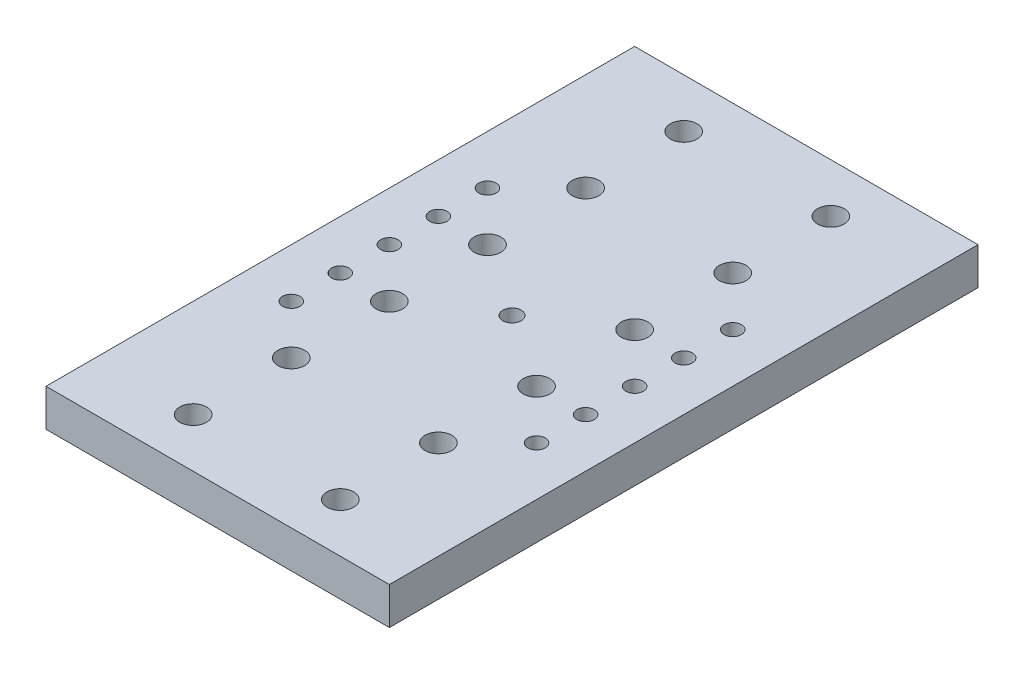
SolidWorks part; units mm, degrees
ref_plane "Front Plane" through (0, 0, 0) normal (0, 0, 1) x (1, 0, 0)
ref_plane "Top Plane" through (0, 0, 0) normal (0, 1, 0) x (1, 0, 0)
ref_plane "Right Plane" through (0, 0, 0) normal (1, 0, 0) x (0, 0, -1)
sketch "Sketch1" plane through (0, 0, 0) normal (0, 1, 0) x (1, 0, 0)
  line L0 (-19.05, 76.2) -> (-19.05, -76.2) construction
  line L1 (-44.45, -76.2) -> (44.45, -76.2)
  line L2 (-44.45, -76.2) -> (-44.45, 76.2)
  line L3 (-44.45, 76.2) -> (44.45, 76.2)
  line L4 (44.45, -76.2) -> (44.45, 76.2)
  line L5 (-44.45, -76.2) -> (44.45, 76.2) construction
  line L6 (-44.45, 76.2) -> (44.45, -76.2) construction
  line L7 (19.05, 76.2) -> (19.05, -76.2) construction
  line L8 (-31.75, 76.2) -> (-31.75, -76.2) construction
  line L9 (31.75, 76.2) -> (31.75, -76.2) construction
  line L10 (-44.45, 12.7) -> (44.45, 12.7) construction
  line L11 (-44.45, -12.7) -> (44.45, -12.7) construction
  line L12 (-44.45, 38.1) -> (44.45, 38.1) construction
  line L13 (-44.45, 63.5) -> (44.45, 63.5) construction
  line L14 (-44.45, -38.1) -> (44.45, -38.1) construction
  line L15 (-44.45, -63.5) -> (44.45, -63.5) construction
  line L16 (-44.45, 25.4) -> (44.45, 25.4) construction
  line L17 (-44.45, -25.4) -> (44.45, -25.4) construction
  line L18 (-44.45, 0) -> (44.45, 0) construction
  circle A0 centre (0, 0) radius 2.3813
  point P0 (0, 0)
  dimension "D3" = 25.4
  dimension "D1" = 152.4
  dimension "D2" = 88.9
  dimension "D4" = 38.1
  dimension "D5" = 12.7
  dimension "D6" = 63.5
  dimension "D7" = 12.7
  dimension "D8" = 12.7
  dimension "D9" = 25.4
  dimension "D10" = 25.4
  dimension "D11" = 25.4
  dimension "D12" = 25.4
  dimension "D13" = 12.7
  dimension "D14" = 12.7
extrude "Boss-Extrude1" add sketch "Sketch1" along normal blind 9.652
hole_wizard "5/16-24 Tapped Hole1" positions "Sketch3" profile "Sketch2" tap size "5/16-24" standard "ANSI Inch" end condition through all
sketch "Sketch3" plane through (0, 9.652, 0) normal (0, 1, 0) x (1, 0, 0)
  line L0 (19.05, 76.2) -> (19.05, -76.2) construction
  line L1 (-44.45, 63.5) -> (44.45, 63.5) construction
  line L2 (-19.05, 76.2) -> (-19.05, -76.2) construction
  line L3 (-44.45, 38.1) -> (44.45, 38.1) construction
  line L4 (-44.45, 12.7) -> (44.45, 12.7) construction
  line L5 (-44.45, -12.7) -> (44.45, -12.7) construction
  line L6 (-44.45, -38.1) -> (44.45, -38.1) construction
  line L7 (-44.45, -63.5) -> (44.45, -63.5) construction
  point P0 (19.05, 63.5)
  point P6 (-19.05, 63.5)
  point P10 (-19.05, 38.1)
  point P14 (19.05, 38.1)
  point P16 (19.05, 12.7)
  point P20 (19.05, -12.7)
  point P24 (19.05, -38.1)
  point P28 (19.05, -63.5)
  point P32 (-19.05, 12.7)
  point P34 (-19.05, -12.7)
  point P36 (-19.05, -38.1)
  point P38 (-19.05, -63.5)
sketch "Sketch2" plane through (19.05, 9.652, -63.5) normal (1, 0, 0) x (0, 0, 1)
  line L0 (0, 0) -> (0, 9.652)
  line L1 (0, 9.652) -> (3.4544, 9.652)
  line L2 (3.4544, 9.652) -> (3.4544, 0)
  line L5 (3.4544, 0) -> (0, 0)
  line L11 (0, -6.35) -> (0, 107.95) construction
  dimension "Thru Tap Drill Dia." = 6.9088
  dimension "Thru Tap Drill Depth" = 9.652
cosmetic thread "Hole Thread1" parameters "D2"=7.9375
cosmetic thread "Hole Thread2" parameters "D2"=7.9375
cosmetic thread "Hole Thread3" parameters "D2"=7.9375
cosmetic thread "Hole Thread4" parameters "D2"=7.9375
cosmetic thread "Hole Thread5" parameters "D2"=7.9375
cosmetic thread "Hole Thread6" parameters "D2"=7.9375
cosmetic thread "Hole Thread7" parameters "D2"=7.9375
cosmetic thread "Hole Thread8" parameters "D2"=7.9375
cosmetic thread "Hole Thread9" parameters "D2"=7.9375
cosmetic thread "Hole Thread10" parameters "D2"=7.9375
cosmetic thread "Hole Thread11" parameters "D2"=7.9375
cosmetic thread "Hole Thread12" parameters "D2"=7.9375
hole_wizard "#12-24 Tapped Hole1" positions "Sketch5" profile "Sketch4" tap size "#12-24" standard "ANSI Inch" end condition through all
sketch "Sketch5" plane through (0, 9.652, 0) normal (0, 1, 0) x (1, 0, 0)
  line L0 (-31.75, 76.2) -> (-31.75, -76.2) construction
  line L1 (31.75, 76.2) -> (31.75, -76.2) construction
  line L2 (-44.45, 12.7) -> (44.45, 12.7) construction
  line L3 (-44.45, 25.4) -> (44.45, 25.4) construction
  line L4 (-44.45, -12.7) -> (44.45, -12.7) construction
  line L5 (-44.45, -25.4) -> (44.45, -25.4) construction
  point P0 (-31.75, 0)
  point P4 (31.75, 0)
  point P8 (-31.75, 12.7)
  point P12 (-31.75, 25.4)
  point P16 (31.75, 25.4)
  point P18 (31.75, 12.7)
  point P20 (31.75, -12.7)
  point P24 (31.75, -25.4)
  point P28 (-31.75, -12.7)
  point P29 (-31.75, -25.4)
sketch "Sketch4" plane through (-31.75, 9.652, 0) normal (1, 0, 0) x (0, 0, 1)
  line L0 (0, 0) -> (0, 9.652)
  line L1 (0, 9.652) -> (2.2479, 9.652)
  line L2 (2.2479, 9.652) -> (2.2479, 0)
  line L5 (2.2479, 0) -> (0, 0)
  line L11 (0, -6.35) -> (0, 107.95) construction
  dimension "Thru Tap Drill Dia." = 4.4958
  dimension "Thru Tap Drill Depth" = 9.652
cosmetic thread "Hole Thread13" parameters "D2"=5.4864
cosmetic thread "Hole Thread14" parameters "D2"=5.4864
cosmetic thread "Hole Thread15" parameters "D2"=5.4864
cosmetic thread "Hole Thread16" parameters "D2"=5.4864
cosmetic thread "Hole Thread17" parameters "D2"=5.4864
cosmetic thread "Hole Thread18" parameters "D2"=5.4864
cosmetic thread "Hole Thread19" parameters "D2"=5.4864
cosmetic thread "Hole Thread20" parameters "D2"=5.4864
cosmetic thread "Hole Thread21" parameters "D2"=5.4864
cosmetic thread "Hole Thread22" parameters "D2"=5.4864
